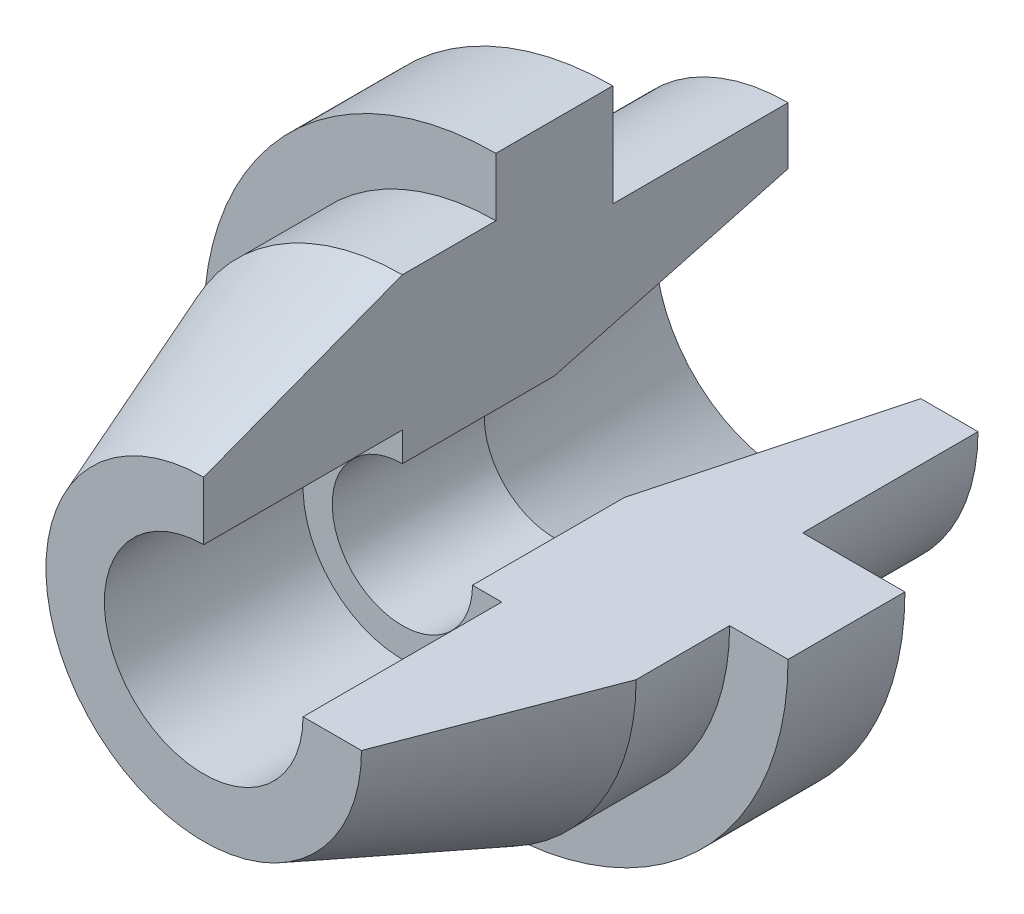
SolidWorks part; units mm, degrees
ref_plane "Front Plane" through (0, 0, 0) normal (0, 0, 1) x (1, 0, 0)
ref_plane "Top Plane" through (0, 0, 0) normal (0, 1, 0) x (1, 0, 0)
ref_plane "Right Plane" through (0, 0, 0) normal (1, 0, 0) x (0, 0, -1)
sketch "Sketch1" plane through (0, 0, 0) normal (1, 0, 0) x (0, 0, -1)
  line L11 (0, 0) -> (0, 27)
  line L12 (0, 27) -> (34, 40)
  line L13 (34, 40) -> (50, 40)
  line L14 (50, 40) -> (50, 50)
  line L15 (50, 50) -> (70, 50)
  line L16 (70, 50) -> (70, 32.5)
  line L17 (70, 32.5) -> (100, 32.5)
  line L18 (100, 32.5) -> (100, 0)
  line L19 (100, 0) -> (0, 0)
  point P2 (0, 12.2772)
  point P10 (0, 0)
  dimension "D1" = 100
  dimension "D2" = 20
  dimension "D3" = 32.5
  dimension "D4" = 50
  dimension "D5" = 27
  dimension "D6" = 40
  dimension "D7" = 34
  dimension "D8" = 30
revolve "Revolve1" add sketch "Sketch1" angle 270 about L19
sketch "Sketch3" plane through (0, 0, 0) normal (1, 0, 0) x (0, 0, -1)
  line L0 (0, 17) -> (0, 0)
  line L1 (0, 27) -> (0, 0) construction
  line L2 (0, 0) -> (100, 0)
  line L3 (100, 0) -> (100, 22.718)
  line L4 (100, 0) -> (100, 32.5) construction
  line L5 (100, 22.718) -> (60, 12)
  line L6 (60, 12) -> (34, 12)
  line L7 (34, 12) -> (34, 17)
  line L8 (34, 17) -> (0, 17)
  dimension "D1" = 15
  dimension "D2" = 60
  dimension "D3" = 34
  dimension "D4" = 17
  dimension "D5" = 12
revolve "Cut-Revolve1" cut sketch "Sketch3" angle 360 about L2
